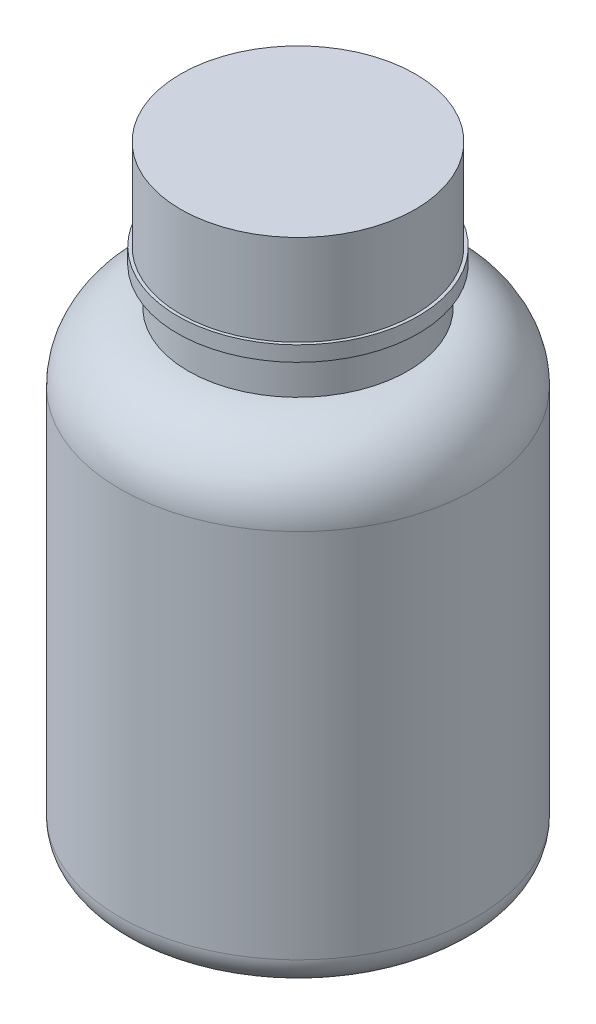
SolidWorks part; units mm, degrees
ref_plane "前视基准面" through (0, 0, 0) normal (0, 0, 1) x (1, 0, 0)
ref_plane "上视基准面" through (0, 0, 0) normal (0, 1, 0) x (1, 0, 0)
ref_plane "右视基准面" through (0, 0, 0) normal (1, 0, 0) x (0, 0, -1)
other "Configuration Table"
sketch "草图1" plane through (0, 0, 0) normal (0, 0, 1) x (1, 0, 0)
  line L0 (0, -4.7776) -> (0, 4.7776) construction
  line L1 (-15.909, 44) -> (-15.5, 44) construction
  line L2 (-19.5, -25) -> (19.5, -25)
  line L3 (-23.5, -21) -> (-23.5, 25)
  line L5 (23.5, -21) -> (23.5, 25)
  line L6 (-23.5, -25) -> (23.5, 25) construction
  line L7 (-23.5, 25) -> (23.5, -25) construction
  line L9 (-15.5, 44) -> (-15.5, 56)
  line L10 (-15.5, 56) -> (15.5, 56)
  line L11 (15.5, 44) -> (15.5, 56)
  line L12 (-15.5, 44) -> (15.5, 56) construction
  line L13 (-15.5, 56) -> (15.5, 44) construction
  line L16 (15.909, 44) -> (15.5, 44)
  line L17 (15.909, 44) -> (15.909, 42)
  line L18 (15.909, 42) -> (14.5, 42)
  line L19 (-15.909, 44) -> (-15.909, 42)
  line L20 (0, 0) -> (0, 73.7116) construction
  line L23 (-14.5, 42) -> (-14.5, 37)
  line L25 (14.5, 42) -> (14.5, 37)
  line L26 (23.5, 28) -> (23.5, 25)
  line L28 (-23.5, 28) -> (-23.5, 25)
  line L29 (-14.5, 42) -> (-15.909, 42)
  line L30 (-15.5, 44) -> (-15.909, 44)
  line L31 (15.5, 44) -> (15.909, 44) construction
  line L32 (0, 60.4044) -> (0, -40.3542)
  arc A2 (-19.5, -25) -> (-23.5, -21) centre (-19.5, -21) cw
  arc A3 (19.5, -25) -> (23.5, -21) centre (19.5, -21) ccw
  arc A4 (-14.5, 37) -> (-23.5, 28) centre (-14.5, 28) ccw
  arc A5 (14.5, 37) -> (23.5, 28) centre (14.5, 28) cw
  point P0 (0, 0)
  point P4 (0, 0)
  point P10 (0, 50)
  point P17 (0, 44)
  dimension "D8" = 4
  dimension "D11" = 9
  dimension "D1" = 47
  dimension "D2" = 50
  dimension "D3" = 81
  dimension "D4" = 31
  dimension "D5" = 12
  dimension "D6" = 2
  dimension "D7" = 0
revolve "旋转1" add sketch "草图1" angle 360 about L20
